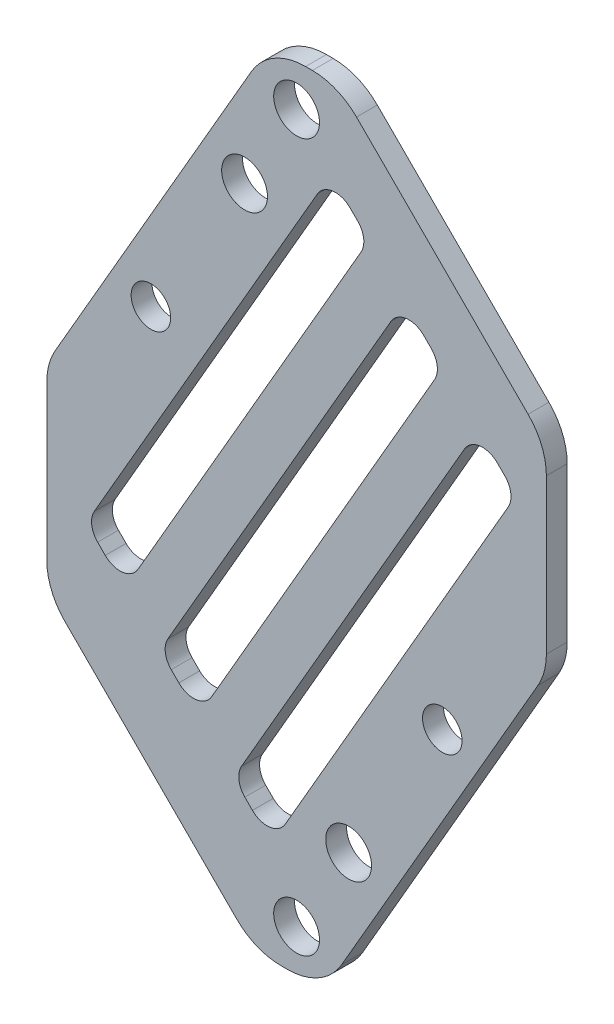
SolidWorks part; units mm, degrees
ref_plane "前视基准面" through (0, 0, 0) normal (0, 0, 1) x (1, 0, 0)
ref_plane "上视基准面" through (0, 0, 0) normal (0, 1, 0) x (1, 0, 0)
ref_plane "右视基准面" through (0, 0, 0) normal (1, 0, 0) x (0, 0, -1)
sketch "草图1" plane through (0, 0, 0) normal (0, 0, 1) x (1, 0, 0)
  line L1 (0, 0) -> (200, 0)
  line L2 (0, 0) -> (0, 380)
  line L3 (0, 380) -> (200, 380)
  line L4 (200, 0) -> (200, 380)
  dimension "D1" = 200
  dimension "D2" = 380
extrude "凸台-拉伸1" add sketch "草图1" along normal blind 10
sketch "草图2" plane through (0, 0, 10) normal (0, 0, 1) x (1, 0, 0)
  line L0 (200, 0) -> (200, 380) construction
  line L1 (120, 20) -> (145, 63.3013) construction
  line L2 (0, 0) -> (200, 0) construction
  circle A0 centre (120, 20) radius 11
  circle A1 centre (145, 63.3013) radius 11
  dimension "D1" = 22
  dimension "D2" = 50
  dimension "D3" = 80
  dimension "D4" = 30
  dimension "D5" = 20
extrude "切除-拉伸1" cut sketch "草图2" against normal through all
sketch "草图3" plane through (0, 0, 10) normal (0, 0, 1) x (1, 0, 0)
  circle A0 centre (50, 243) radius 8
  circle A1 centre (120, 20) radius 11 construction
  dimension "D1" = 16
  dimension "D2" = 223
  dimension "D3" = 70
extrude "切除-拉伸2" cut sketch "草图3" against normal through all
sketch "草图4" plane through (0, 0, 10) normal (0, 0, 1) x (1, 0, 0)
  circle A0 centre (50, 243) radius 9.5
  dimension "D1" = 19
extrude "切除-拉伸3" cut sketch "草图4" against normal blind 6 contours A0
sketch "草图5" plane through (0, 0, 0) normal (0, 0, -1) x (-1, 0, 0)
  circle A0 centre (-50, 243) radius 9.5
  dimension "D1" = 19
extrude "切除-拉伸4" cut sketch "草图5" against normal blind 6
sketch "草图6" plane through (0, 0, 10) normal (0, 0, 1) x (1, 0, 0)
  line L0 (200, 380) -> (0, 380) construction
  line L2 (200, 0) -> (200, 380) construction
  line L3 (120, 360) -> (95, 316.6987) construction
  circle A0 centre (95, 316.6987) radius 11
  circle A1 centre (120, 360) radius 11
  dimension "D1" = 22
  dimension "D2" = 22
  dimension "D5" = 80
  dimension "D3" = 50
  dimension "D4" = 20
  dimension "D6" = 60
extrude "切除-拉伸5" cut sketch "草图6" against normal through all
sketch "草图7" plane through (0, 0, 10) normal (0, 0, 1) x (1, 0, 0)
  circle A0 centre (190, 137) radius 8
  circle A1 centre (120, 360) radius 11 construction
  dimension "D1" = 16
  dimension "D2" = 223
  dimension "D3" = 70
extrude "切除-拉伸6" cut sketch "草图7" against normal through all contours A0
sketch "草图8" plane through (0, 0, 10) normal (0, 0, 1) x (1, 0, 0)
  circle A0 centre (190, 137) radius 9.5
  dimension "D1" = 19
extrude "切除-拉伸7" cut sketch "草图8" against normal blind 6
sketch "草图9" plane through (0, 0, 0) normal (0, 0, -1) x (-1, 0, 0)
  circle A0 centre (-190, 137) radius 9.5
  dimension "D1" = 19
extrude "切除-拉伸8" cut sketch "草图9" against normal blind 6
sketch "草图10" plane through (0, 0, 10) normal (0, 0, 1) x (1, 0, 0)
  line L1 (200, 380) -> (240, 380)
  line L2 (200, 380) -> (200, 0)
  line L3 (200, 0) -> (240, 0)
  line L4 (240, 380) -> (240, 0)
  dimension "D1" = 40
extrude "凸台-拉伸3" add sketch "草图10" against normal up to surface (10 mm away) up to face at (180.5, 137, 0)
sketch "草图11" plane through (0, 0, 10) normal (0, 0, 1) x (1, 0, 0)
  line L0 (240, 185.3294) -> (133, 0)
  line L1 (240, 0) -> (240, 380) construction
  line L2 (0, 0) -> (240, 0) construction
  line L3 (133, 0) -> (240, 0)
  line L4 (240, 0) -> (240, 185.3294)
  line L5 (0, 380) -> (0, 194.6706)
  line L6 (0, 380) -> (0, 0) construction
  line L7 (0, 194.6706) -> (107, 380)
  line L8 (240, 380) -> (0, 380) construction
  line L9 (107, 380) -> (0, 380)
  dimension "D1" = 60
  dimension "D2" = 107
extrude "切除-拉伸9" cut sketch "草图11" against normal through all
chamfer "倒角1" distance 100 angle 45 2 edges at (240, 380, 5) (0, 0, 5)
fillet "圆角1" radius 30 8 edges at (0, 194.6706, 5) (0, 100, 5) (100, 0, 5) (133, 0, 5) (240, 185.3294, 5) (240, 280, 5) (140, 380, 5) (107, 380, 5)
sketch "草图12" plane through (0, 0, 10) normal (0, 0, 1) x (1, 0, 0)
  line L6 (28.0821, 128.4865) -> (24.4218, 132.1467)
  line L8 (145.7072, 331.8664) -> (149.3674, 328.2062)
  line L9 (8.7868, 91.2132) -> (91.2132, 8.7868) construction
  line L10 (231.2132, 288.7868) -> (148.7868, 371.2132) construction
  line L11 (150.9566, 316.1351) -> (43.8134, 130.5576)
  line L12 (129.9759, 329.7953) -> (22.8326, 144.2178)
  line L13 (4.0192, 201.6321) -> (98.3397, 365) construction
  line L14 (165.3312, 294.44) -> (58.188, 108.8625)
  line L15 (63.4374, 93.1311) -> (59.7771, 96.7914)
  line L16 (186.312, 280.7798) -> (79.1687, 95.2022)
  line L17 (181.0625, 296.5111) -> (184.7228, 292.8508)
  line L18 (200.6865, 259.0847) -> (93.5433, 73.5071)
  line L19 (98.7927, 57.7758) -> (95.1325, 61.4361)
  line L20 (221.6673, 245.4244) -> (114.5241, 59.8469)
  line L21 (216.4179, 261.1557) -> (220.0781, 257.4955)
  arc A0 (93.5433, 73.5071) -> (95.1325, 61.4361) centre (102.2035, 68.5071) ccw
  arc A1 (98.7927, 57.7758) -> (114.5241, 59.8469) centre (105.8638, 64.8469) ccw
  arc A2 (221.6673, 245.4244) -> (220.0781, 257.4955) centre (213.007, 250.4244) ccw
  arc A3 (200.6865, 259.0847) -> (216.4179, 261.1557) centre (209.3468, 254.0847) cw
  arc A4 (186.312, 280.7798) -> (184.7228, 292.8508) centre (177.6517, 285.7798) ccw
  arc A5 (165.3312, 294.44) -> (181.0625, 296.5111) centre (173.9914, 289.44) cw
  arc A6 (63.4374, 93.1311) -> (79.1687, 95.2022) centre (70.5085, 100.2022) ccw
  arc A7 (58.188, 108.8625) -> (59.7771, 96.7914) centre (66.8482, 103.8625) ccw
  arc A8 (149.3674, 328.2062) -> (150.9566, 316.1351) centre (142.2964, 321.1351) cw
  arc A9 (129.9759, 329.7953) -> (145.7072, 331.8664) centre (138.6361, 324.7953) cw
  arc A10 (43.8134, 130.5576) -> (28.0821, 128.4865) centre (35.1531, 135.5576) cw
  arc A11 (24.4218, 132.1467) -> (22.8326, 144.2178) centre (31.4929, 139.2178) cw
  dimension "D6" = 10
  dimension "D1" = 45
  dimension "D2" = 40
  dimension "D3" = 30
  dimension "D4" = 25
  dimension "D5" = 3
extrude "切除-拉伸10" cut sketch "草图12" against normal through all
